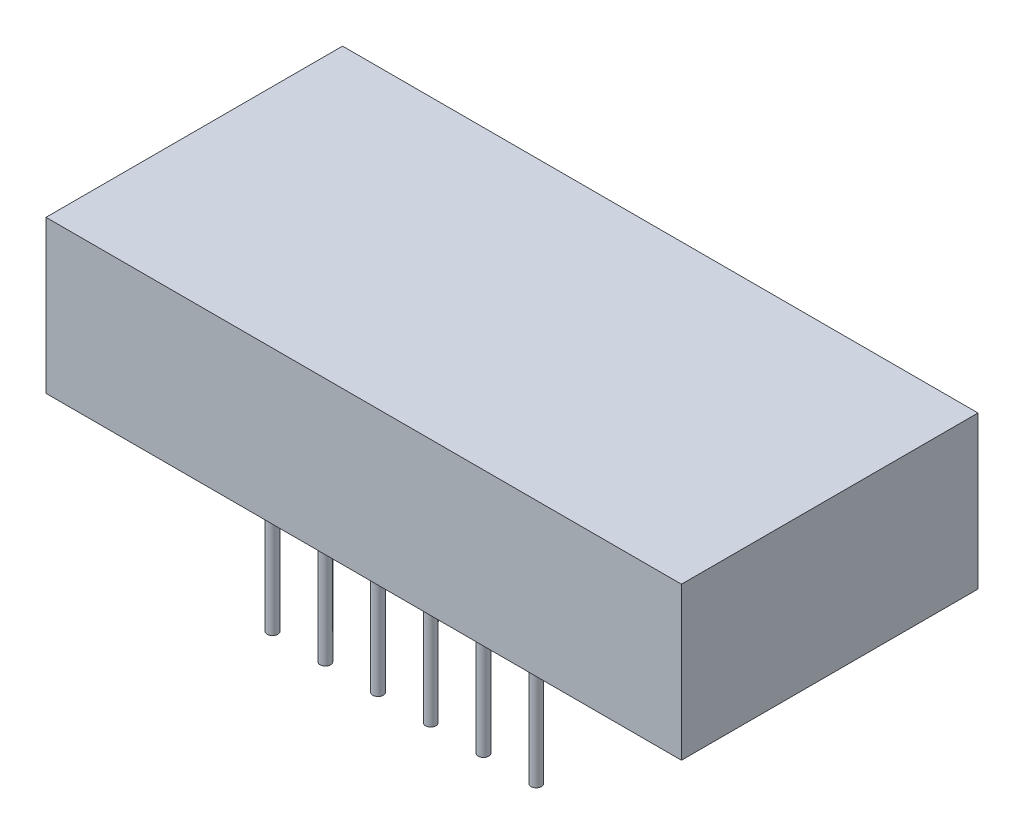
SolidWorks part; units mm, degrees
ref_plane "前视基准面" through (0, 0, 0) normal (0, 0, 1) x (1, 0, 0)
ref_plane "上视基准面" through (0, 0, 0) normal (0, 1, 0) x (1, 0, 0)
ref_plane "右视基准面" through (0, 0, 0) normal (1, 0, 0) x (0, 0, -1)
sketch "草图1" plane through (0, 0, 0) normal (0, 1, 0) x (1, 0, 0)
  line L0 (-29.3463, 0) -> (31.8739, 0) construction
  line L1 (-15, 7) -> (15, 7)
  line L2 (-15, 7) -> (-15, -7)
  line L3 (-15, -7) -> (15, -7)
  line L4 (15, 7) -> (15, -7)
  line L5 (0, 30.3794) -> (0, -29.5342) construction
  dimension "D1" = 30
  dimension "D2" = 14
extrude "拉伸1" add sketch "草图1" along normal blind 7.2
sketch "草图2" plane through (0, 0, 0) normal (0, -1, 0) x (1, 0, 0)
  line L0 (22.7617, 0) -> (-24.809, 0) construction
  line L1 (0, 10.3572) -> (0, -11.9228) construction
  line L2 (5.6198, 5.08) -> (-6.2174, 5.08) construction
  line L3 (5.6198, -5.08) -> (-6.2174, -5.08) construction
  circle A0 centre (6.2247, 5.08) radius 0.25
  circle A1 centre (3.7348, 5.08) radius 0.25
  circle A2 centre (1.2449, 5.08) radius 0.25
  circle A3 centre (-1.2449, 5.08) radius 0.25
  circle A4 centre (-3.7348, 5.08) radius 0.25
  circle A5 centre (-6.2247, 5.08) radius 0.25
  circle A6 centre (-6.2247, -5.08) radius 0.25
  circle A7 centre (-3.7348, -5.08) radius 0.25
  circle A8 centre (-1.2449, -5.08) radius 0.25
  circle A9 centre (1.2449, -5.08) radius 0.25
  circle A10 centre (3.7348, -5.08) radius 0.25
  circle A11 centre (6.2247, -5.08) radius 0.25
  dimension "D1" = 0.5
  dimension "D2" = 10.16
extrude "拉伸2" add sketch "草图2" along normal blind 6.3
